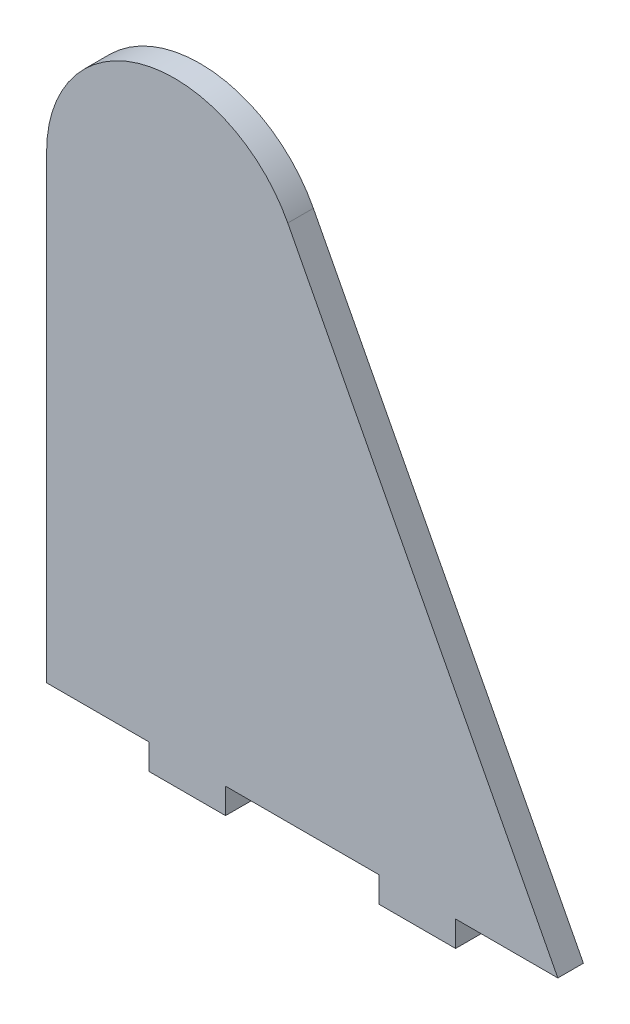
SolidWorks part; units mm, degrees
ref_plane "Front Plane" through (0, 0, 0) normal (0, 0, 1) x (1, 0, 0)
ref_plane "Top Plane" through (0, 0, 0) normal (0, 1, 0) x (1, 0, 0)
ref_plane "Right Plane" through (0, 0, 0) normal (1, 0, 0) x (0, 0, -1)
sketch "Sketch1" plane through (0, 0, 0) normal (0, 0, 1) x (1, 0, 0)
  line L0 (0, 89.9316) -> (0, 0)
  line L1 (0, 0) -> (20, 0)
  line L2 (100, 0) -> (47.1753, 101.4754)
  line L3 (80, 0) -> (100, 0)
  line L5 (20, 0) -> (20, -5)
  line L6 (20, -5) -> (35, -5)
  line L7 (35, 0) -> (35, -5)
  line L8 (35, 0) -> (65, 0)
  line L9 (65, 0) -> (65, -5)
  line L10 (65, -5) -> (80, -5)
  line L11 (80, 0) -> (80, -5)
  arc A0 (0, 89.9316) -> (47.1753, 101.4754) centre (25, 89.9316) cw
  dimension "D7" = 25
  dimension "D1" = 62.5
  dimension "D2" = 100
  dimension "D3" = 15
  dimension "D4" = 5
  dimension "D5" = 20
  dimension "D6" = 30
extrude "Boss-Extrude1" add sketch "Sketch1" along normal blind 5
